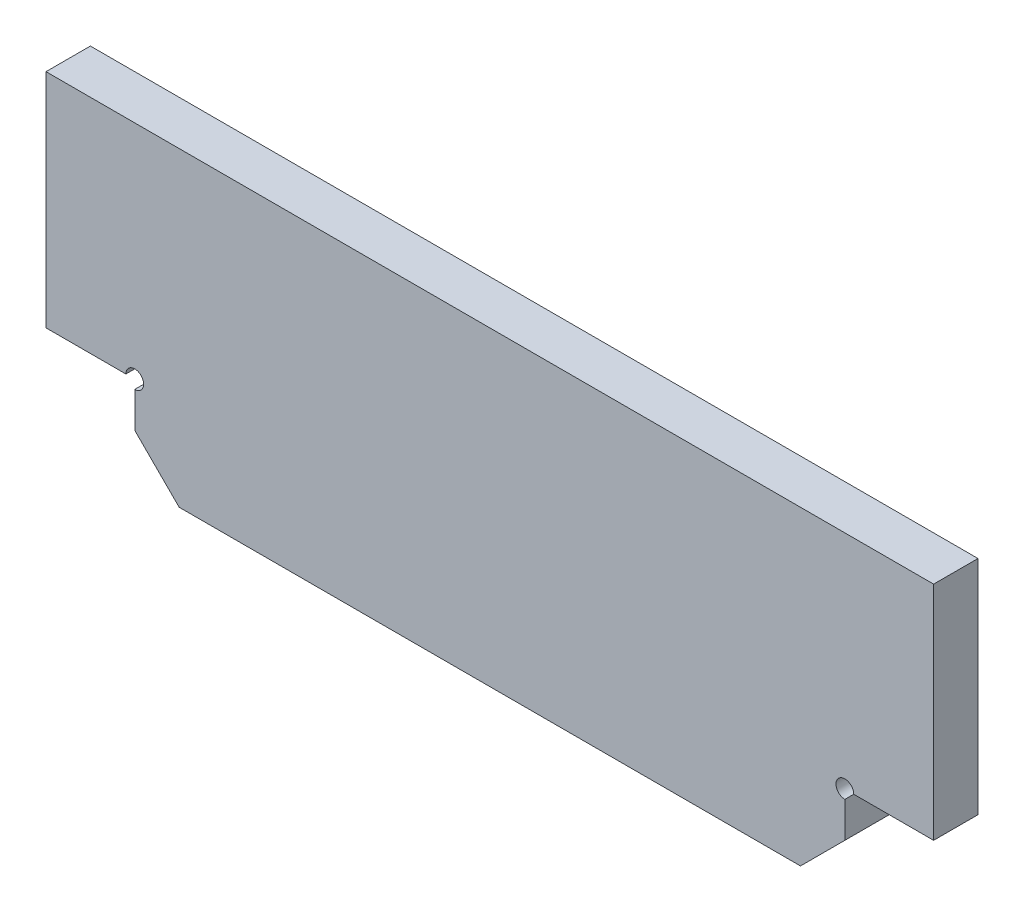
SolidWorks part; units mm, degrees
ref_plane "前基準面" through (0, 0, 0) normal (0, 0, 1) x (1, 0, 0)
ref_plane "上基準面" through (0, 0, 0) normal (0, 1, 0) x (1, 0, 0)
ref_plane "右基準面" through (0, 0, 0) normal (1, 0, 0) x (0, 0, -1)
sketch "草圖1" plane through (0, 0, 0) normal (0, 0, 1) x (1, 0, 0)
  line L0 (-40, 5) -> (-35, 0)
  line L3 (-35, 0) -> (35, 0)
  line L5 (35, 0) -> (40, 5)
  line L6 (-40, 5) -> (-40, 9)
  line L9 (50, 35) -> (-50, 35)
  line L10 (-50, 10) -> (-50, 35)
  line L14 (50, 10) -> (50, 35)
  line L15 (-41, 10) -> (-50, 10)
  line L16 (40, 5) -> (40, 9)
  line L17 (41, 10) -> (50, 10)
  arc A0 (-40, 9) -> (-41, 10) centre (-40, 10) ccw
  arc A1 (41, 10) -> (40, 9) centre (40, 10) ccw
  point P1 (40, 0)
  point P2 (-40, 0)
  point P3 (0, 0)
  point P8 (0, 0)
  point P19 (0, 0)
  point P20 (0, 0)
  point P21 (0, 0)
  point P22 (0, 0)
  dimension "D8" = 1
  dimension "D1" = 80
  dimension "D2" = 100
  dimension "D3" = 25
  dimension "D6" = 5
  dimension "D7" = 5
extrude "填料-伸長1" add sketch "草圖1" along normal mid plane 5 contours L9 L10 L15 A0 L6 L0 L3 L5 L16 A1 L17 L14
